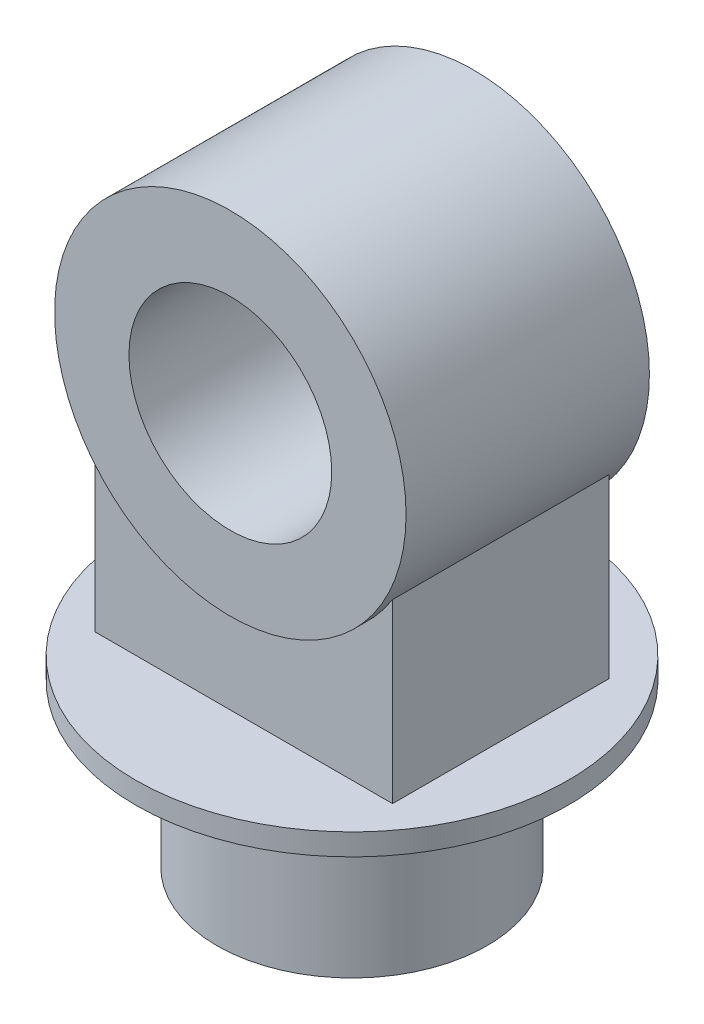
SolidWorks part; units mm, degrees
ref_plane "Front Plane" through (0, 0, 0) normal (0, 0, 1) x (1, 0, 0)
ref_plane "Top Plane" through (0, 0, 0) normal (0, 1, 0) x (1, 0, 0)
ref_plane "Right Plane" through (0, 0, 0) normal (1, 0, 0) x (0, 0, -1)
sketch "Sketch1" plane through (0, 0, 0) normal (0, 1, 0) x (1, 0, 0)
  circle A0 centre (0, 0) radius 100
extrude "Boss-Extrude3" add sketch "Sketch1" along normal blind 120
sketch "Sketch4" plane through (0, 120, 0) normal (0, 1, 0) x (1, 0, 0)
  circle A0 centre (0, 0) radius 160
extrude "Boss-Extrude4" add sketch "Sketch4" along normal blind 16
sketch "Sketch5" plane through (0, 0, 0) normal (0, 0, 1) x (1, 0, 0)
  line L0 (160, 136) -> (-160, 136) construction
  circle A0 centre (0, 336) radius 75
  circle A1 centre (0, 336) radius 130
  dimension "D1" = 200
  dimension "D2" = 150
  dimension "D3" = 260
extrude "Boss-Extrude5" add sketch "Sketch5" along normal mid plane 180 separate body
sketch "Sketch6" plane through (0, 136, 0) normal (0, 1, 0) x (1, 0, 0)
  line L1 (-110, 80) -> (110, 80)
  line L2 (-110, 80) -> (-110, -80)
  line L3 (-110, -80) -> (110, -80)
  line L4 (110, 80) -> (110, -80)
  line L5 (-110, 80) -> (110, -80) construction
  line L6 (-110, -80) -> (110, 80) construction
  point P0 (0, 0)
  dimension "D1" = 160
  dimension "D2" = 220
extrude "Boss-Extrude6" add sketch "Sketch6" along normal up to surface (130.718 mm away)
